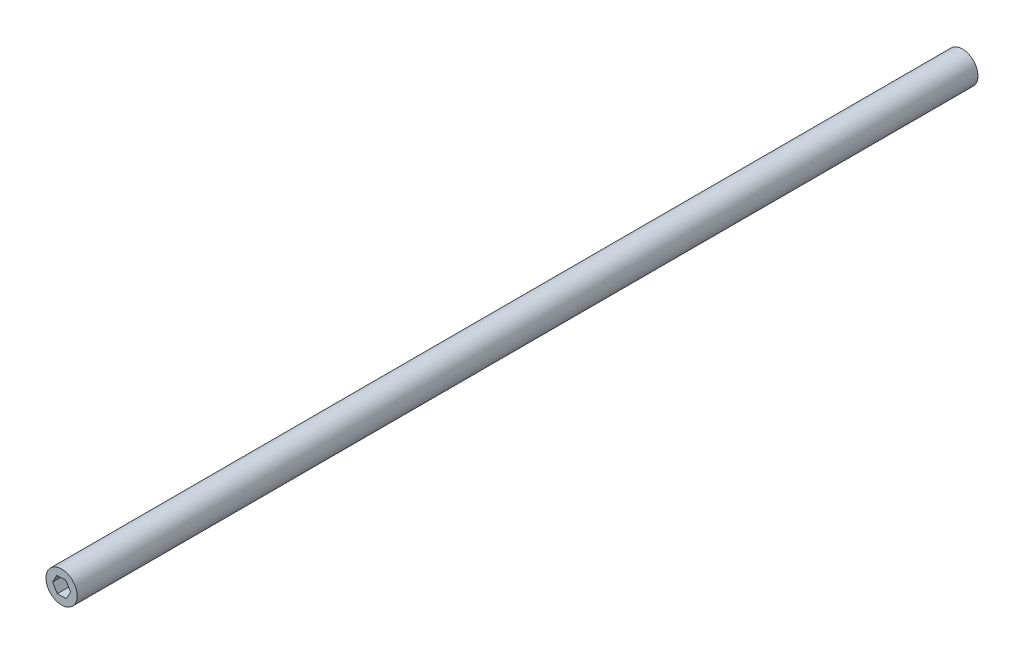
SolidWorks part; units mm, degrees
ref_plane "Front Plane" through (0, 0, 0) normal (0, 0, 1) x (1, 0, 0)
ref_plane "Top Plane" through (0, 0, 0) normal (0, 1, 0) x (1, 0, 0)
ref_plane "Right Plane" through (0, 0, 0) normal (1, 0, 0) x (0, 0, -1)
sketch "Sketch1" plane through (0, 0, 0) normal (0, 0, 1) x (1, 0, 0)
  line L1 (3.8291, -6.2531) -> (7.3299, 0.1895)
  line L2 (7.3299, 0.1895) -> (3.5008, 6.4426)
  line L3 (3.5008, 6.4426) -> (-3.8291, 6.2531)
  line L4 (-3.8291, 6.2531) -> (-7.3299, -0.1895)
  line L5 (-7.3299, -0.1895) -> (-3.5008, -6.4426)
  line L6 (-3.5008, -6.4426) -> (3.8291, -6.2531)
  circle A0 centre (0, 0) radius 12.7
  circle A1 centre (0, 0) radius 6.35 construction
  dimension "D1" = 25.4
  dimension "D2" = 12.7
extrude "Boss-Extrude1" add sketch "Sketch1" along normal blind 732.282
